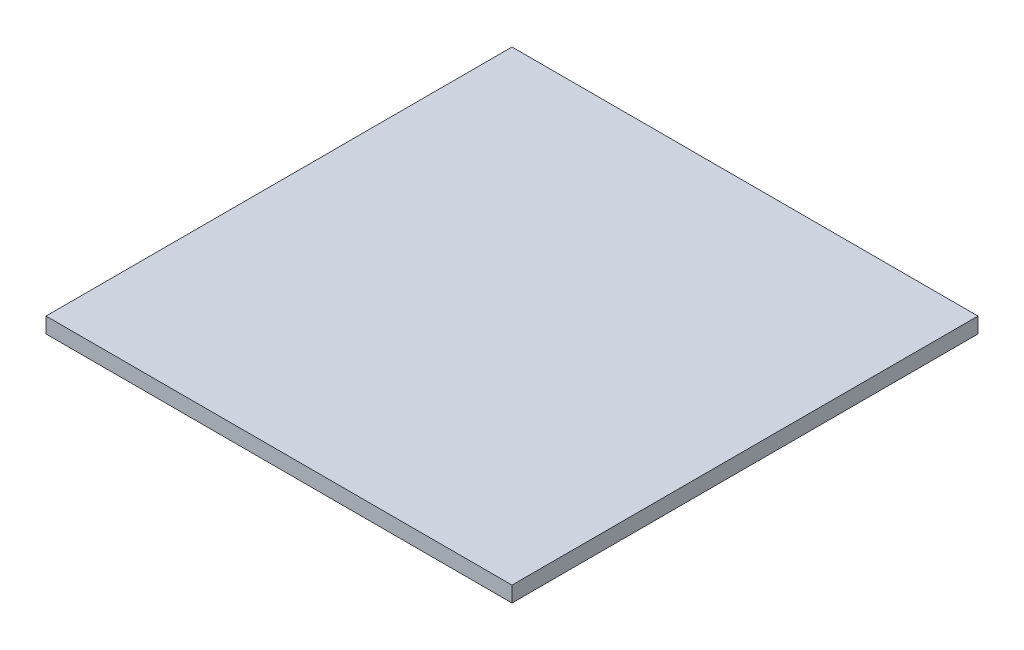
SolidWorks part; units mm, degrees
ref_plane "Alzado" through (0, 0, 0) normal (0, 0, 1) x (1, 0, 0)
ref_plane "Planta" through (0, 0, 0) normal (0, 1, 0) x (1, 0, 0)
ref_plane "Vista lateral" through (0, 0, 0) normal (1, 0, 0) x (0, 0, -1)
sketch "Croquis1" plane through (0, 0, 0) normal (0, 1, 0) x (1, 0, 0)
  line L1 (0, 0) -> (30, 0)
  line L2 (0, 0) -> (0, 30)
  line L3 (0, 30) -> (30, 30)
  line L4 (30, 0) -> (30, 30)
  dimension "D1" = 30
extrude "Saliente-Extruir1" add sketch "Croquis1" along normal blind 1
